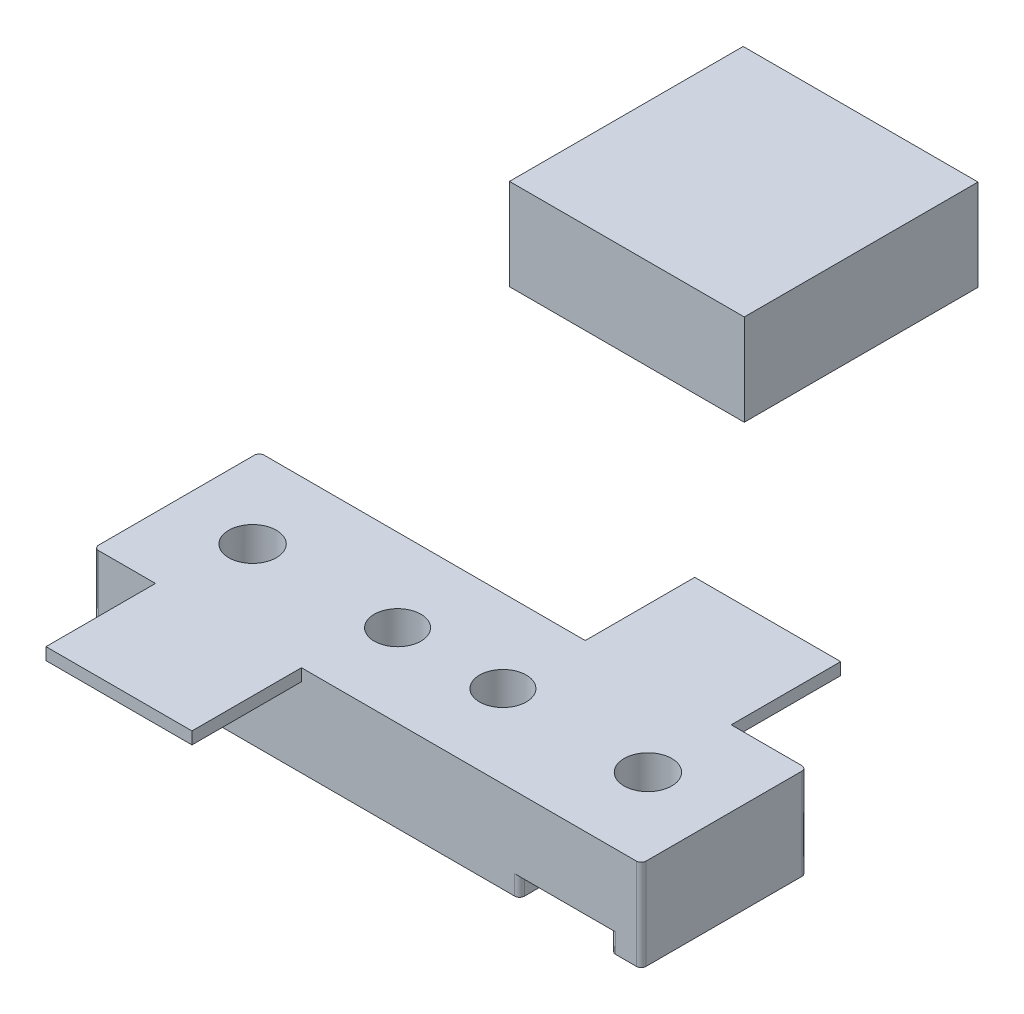
SolidWorks part; units mm, degrees
material "6061-T6 (SS)"
ref_plane "Front Plane" through (0, 0, 0) normal (0, 0, 1) x (1, 0, 0)
ref_plane "Top Plane" through (0, 0, 0) normal (0, 1, 0) x (1, 0, 0)
ref_plane "Right Plane" through (0, 0, 0) normal (1, 0, 0) x (0, 0, -1)
sketch "Sketch1" plane through (0, 0, 0) normal (0, 1, 0) x (1, 0, 0)
  line L0 (-7.9375, 0) -> (7.9375, 0) construction
  line L1 (-28.575, 8.636) -> (-28.575, -8.636)
  line L2 (-28.575, 8.636) -> (28.575, 8.636)
  line L3 (-28.575, -8.636) -> (28.575, -8.636)
  line L4 (28.575, 8.636) -> (28.575, -8.636)
  line L5 (28.575, 8.636) -> (-28.575, -8.636) construction
  circle A0 centre (-5.4991, 0) radius 2.4384
  circle A1 centre (5.4991, 0) radius 2.4384
  dimension "D1" = 4.8768
  dimension "D2" = 15.875
  dimension "D3" = 57.15
  dimension "D4" = 17.272
extrude "Boss-Extrude1" add sketch "Sketch1" along normal blind 9.525
hole_wizard "#10 Clearance Hole1" positions "Sketch2" profile "Sketch3" hole size "#10" standard "ANSI Inch" end condition through all
sketch "Sketch2" plane through (0, 9.525, 0) normal (0, 1, 0) x (1, 0, 0)
  line L1 (-20.6375, 0) -> (20.6375, 0) construction
  point P0 (-20.6375, 0)
  point P2 (20.6375, 0)
  dimension "D1" = 41.275
sketch "Sketch3" plane through (-20.6375, 9.525, 0) normal (1, 0, 0) x (0, 0, 1)
  line L0 (0, 0) -> (0, 9.525)
  line L1 (0, 9.525) -> (2.4892, 9.525)
  line L2 (2.4892, 9.525) -> (2.4892, 0)
  line L5 (2.4892, 0) -> (0, 0)
  line L11 (0, -6.35) -> (0, 107.95) construction
  dimension "Thru Hole Dia." = 4.9784
  dimension "Thru Hole Depth" = 9.525
sketch "Sketch4" plane through (0, 0, 0) normal (0, -1, 0) x (1, 0, 0)
  line L0 (-25.4, -8.636) -> (-25.4, 8.636)
  line L1 (-25.4, -8.636) -> (-15.875, -8.636)
  line L2 (-25.4, 8.636) -> (-15.875, 8.636)
  line L3 (-15.875, -8.636) -> (-15.875, 8.636)
  line L4 (-25.4, 0) -> (-15.875, 0) construction
  line L5 (-28.575, 8.636) -> (28.575, 8.636) construction
  circle A0 centre (-20.6375, 0) radius 2.4892 construction
  circle A1 centre (-5.4991, 0) radius 5.334 construction
  point P6 (-20.6375, 0)
  dimension "D3" = 10.668
  dimension "D1" = 9.525
extrude "Cut-Extrude1" cut sketch "Sketch4" against normal blind 2.032
mirror "Mirror1" about plane through (0, 0, 0) normal (1, 0, 0) of "Cut-Extrude1"
fillet "Fillet1" radius 0.508 12 edges at (-25.4, 1.016, 8.636) (25.4, 1.016, 8.636) (-15.875, 1.016, -8.636) (-15.875, 1.016, 8.636) (15.875, 1.016, 8.636) (15.875, 1.016, -8.636) (25.4, 1.016, -8.636) (-25.4, 1.016, -8.636) (-28.575, 4.7625, -8.636) (-28.575, 4.7625, 8.636) (28.575, 4.7625, 8.636) (28.575, 4.7625, -8.636)
sketch "Sketch5" plane through (0, 9.525, 0) normal (0, 1, 0) x (1, 0, 0)
  line L1 (-15.4973, 70.5979) -> (-40.0139, 70.5979)
  line L2 (-15.4973, 70.5979) -> (-15.4973, 46.1961)
  line L3 (-15.4973, 46.1961) -> (-40.0139, 46.1961)
  line L4 (-40.0139, 70.5979) -> (-40.0139, 46.1961)
  line L5 (-15.4973, 70.5979) -> (-40.0139, 46.1961) construction
  line L6 (-15.4973, 46.1961) -> (-40.0139, 70.5979) construction
  point P0 (-27.7556, 58.397)
extrude "Boss-Extrude2" add sketch "Sketch5" against normal up to surface (9.525 mm away) separate body up to face at (5.4991, 0, 2.4384)
sketch "Sketch6" plane through (0, 9.525, 0) normal (0, 1, 0) x (1, 0, 0)
  line L0 (5.4591, 8.636) -> (20.6991, 8.636)
  line L1 (5.4591, 8.636) -> (5.4591, 20.066)
  line L2 (20.6991, 8.636) -> (20.6991, 20.066)
  line L3 (5.4591, 20.066) -> (20.6991, 20.066)
  line L4 (28.067, 8.636) -> (-28.067, 8.636) construction
  line L5 (-22.1403, -8.636) -> (-6.9003, -8.636)
  line L6 (-22.1403, -8.636) -> (-22.1403, -20.066)
  line L7 (-6.9003, -8.636) -> (-6.9003, -20.066)
  line L8 (-22.1403, -20.066) -> (-6.9003, -20.066)
  line L9 (-28.067, -8.636) -> (28.067, -8.636) construction
  dimension "D1" = 15.24
  dimension "D2" = 11.43
extrude "Boss-Extrude3" add sketch "Sketch6" against normal blind 1.27
sketch "Sketch7" plane through (0, 0, 0) normal (0, -1, 0) x (-1, 0, 0)
  line L0 (25.4, -8.128) -> (25.4, 8.128)
  line L2 (20.6375, 12.6289) -> (20.6375, -12.6289) construction
  line L3 (15.367, -12.6289) -> (25.908, -12.6289)
  line L4 (25.4, -8.128) -> (25.4, 8.128) construction
  line L5 (25.908, 8.636) -> (28.067, 8.636) construction
  line L6 (25.908, 12.6289) -> (15.367, 12.6289)
  line L9 (15.367, -8.636) -> (25.908, -8.636) construction
  line L10 (15.875, -8.128) -> (15.875, 8.128)
  line L11 (0, -27.4765) -> (0, 28.0523) construction
  line L12 (25.4, -8.128) -> (25.4, 8.128)
  line L13 (15.875, -8.128) -> (15.875, 8.128)
  line L14 (-25.908, 12.6289) -> (-15.367, 12.6289)
  line L15 (-20.6375, 12.6289) -> (-20.6375, -12.6289) construction
  line L16 (-15.875, -8.128) -> (-15.875, 8.128)
  line L17 (-25.4, -8.128) -> (-25.4, 8.128)
  line L18 (-15.875, -8.128) -> (-15.875, 8.128)
  line L19 (-15.367, -12.6289) -> (-25.908, -12.6289)
  line L20 (-25.4, -8.128) -> (-25.4, 8.128)
  arc A0 (25.908, -12.6289) -> (25.908, -8.636) centre (25.908, -10.6324) ccw
  arc A1 (25.908, -8.636) -> (25.4, -8.128) centre (25.908, -8.128) cw
  arc A2 (25.4, 8.128) -> (25.908, 8.636) centre (25.908, 8.128) cw
  arc A4 (25.4, -8.128) -> (25.908, -8.636) centre (25.908, -8.128) ccw construction
  arc A5 (25.908, 12.6289) -> (25.908, 8.636) centre (25.908, 10.6324) cw
  arc A6 (15.875, 8.128) -> (15.367, 8.636) centre (15.367, 8.128) ccw
  arc A7 (15.367, 12.6289) -> (15.367, 8.636) centre (15.367, 10.6324) ccw
  arc A8 (25.908, 8.636) -> (25.4, 8.128) centre (25.908, 8.128) ccw construction
  arc A9 (15.367, -8.636) -> (15.875, -8.128) centre (15.367, -8.128) ccw
  arc A10 (15.367, -12.6289) -> (15.367, -8.636) centre (15.367, -10.6324) cw
  arc A11 (25.908, -12.6289) -> (25.908, -8.636) centre (25.908, -10.6324) ccw
  arc A12 (25.908, -8.636) -> (25.4, -8.128) centre (25.908, -8.128) cw
  arc A13 (25.908, 12.6289) -> (25.908, 8.636) centre (25.908, 10.6324) cw
  arc A14 (25.4, 8.128) -> (25.908, 8.636) centre (25.908, 8.128) cw
  arc A15 (15.367, 12.6289) -> (15.367, 8.636) centre (15.367, 10.6324) ccw
  arc A16 (15.875, 8.128) -> (15.367, 8.636) centre (15.367, 8.128) ccw
  arc A17 (15.367, -8.636) -> (15.875, -8.128) centre (15.367, -8.128) ccw
  arc A18 (15.367, -12.6289) -> (15.367, -8.636) centre (15.367, -10.6324) cw
  arc A19 (-25.908, 12.6289) -> (-25.908, 8.636) centre (-25.908, 10.6324) ccw
  arc A20 (-25.908, 12.6289) -> (-25.908, 8.636) centre (-25.908, 10.6324) ccw
  arc A21 (-15.367, -12.6289) -> (-15.367, -8.636) centre (-15.367, -10.6324) ccw
  arc A22 (-15.367, -8.636) -> (-15.875, -8.128) centre (-15.367, -8.128) cw
  arc A23 (-15.875, 8.128) -> (-15.367, 8.636) centre (-15.367, 8.128) cw
  arc A24 (-15.367, 12.6289) -> (-15.367, 8.636) centre (-15.367, 10.6324) cw
  arc A25 (-25.4, 8.128) -> (-25.908, 8.636) centre (-25.908, 8.128) ccw
  arc A26 (-25.908, -8.636) -> (-25.4, -8.128) centre (-25.908, -8.128) ccw
  arc A27 (-25.908, -12.6289) -> (-25.908, -8.636) centre (-25.908, -10.6324) cw
  arc A28 (-15.367, -12.6289) -> (-15.367, -8.636) centre (-15.367, -10.6324) ccw
  arc A29 (-15.367, -8.636) -> (-15.875, -8.128) centre (-15.367, -8.128) cw
  arc A30 (-15.367, 12.6289) -> (-15.367, 8.636) centre (-15.367, 10.6324) cw
  arc A31 (-15.875, 8.128) -> (-15.367, 8.636) centre (-15.367, 8.128) cw
  arc A32 (-25.4, 8.128) -> (-25.908, 8.636) centre (-25.908, 8.128) ccw
  arc A33 (-25.908, -8.636) -> (-25.4, -8.128) centre (-25.908, -8.128) ccw
  arc A34 (-25.908, -12.6289) -> (-25.908, -8.636) centre (-25.908, -10.6324) cw
  point P33 (20.6375, -8.636)
  dimension "D1" = 1.9964
sketch "Sketch8" plane through (0, 0, 0) normal (0, -1, 0) x (1, 0, 0)
  line L0 (-28.067, 8.636) -> (28.067, 8.636)
  line L1 (28.575, 8.128) -> (28.575, -8.128)
  line L2 (28.067, -8.636) -> (-28.067, -8.636)
  line L3 (-28.575, -8.128) -> (-28.575, 8.128)
  arc A0 (28.067, 8.636) -> (28.575, 8.128) centre (28.067, 8.128) cw
  arc A1 (28.575, -8.128) -> (28.067, -8.636) centre (28.067, -8.128) cw
  arc A2 (-28.067, -8.636) -> (-28.575, -8.128) centre (-28.067, -8.128) cw
  arc A3 (-28.067, 8.636) -> (-28.575, 8.128) centre (-28.067, 8.128) ccw
